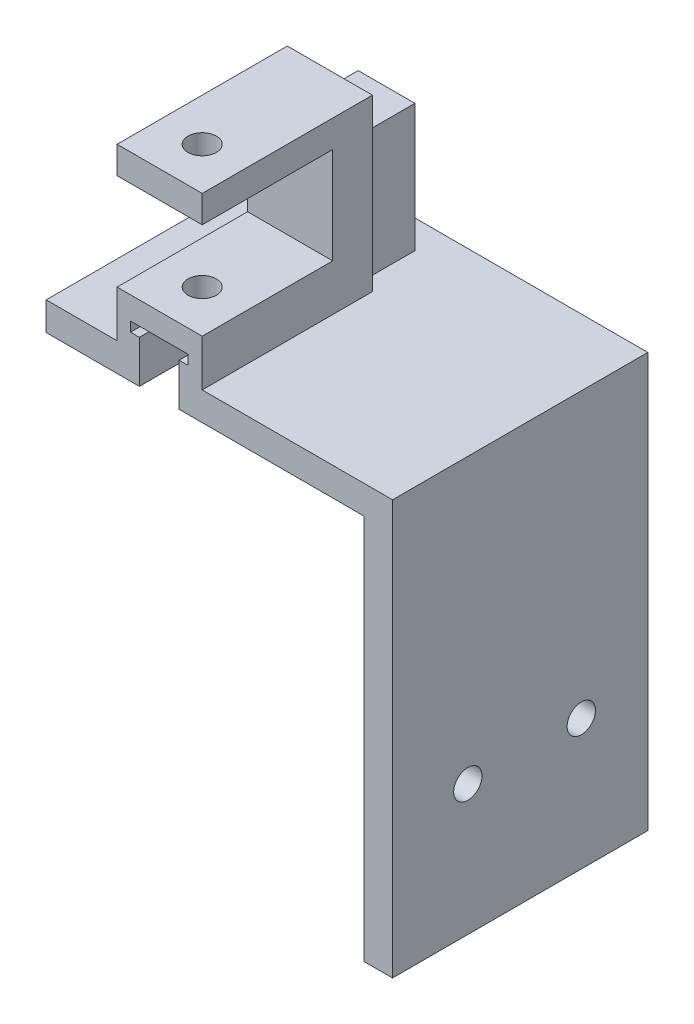
SolidWorks part; units mm, degrees
ref_plane "Front Plane" through (0, 0, 0) normal (0, 0, 1) x (1, 0, 0)
ref_plane "Top Plane" through (0, 0, 0) normal (0, 1, 0) x (1, 0, 0)
ref_plane "Right Plane" through (0, 0, 0) normal (1, 0, 0) x (0, 0, -1)
sketch "Sketch1" plane through (0, 0, 0) normal (0, 1, 0) x (1, 0, 0)
  line L1 (0, 0) -> (61.05, 0)
  line L2 (0, 0) -> (0, 45)
  line L3 (0, 45) -> (61.05, 45)
  line L4 (61.05, 0) -> (61.05, 45)
  dimension "D1" = 61.05
  dimension "D2" = 45
extrude "Boss-Extrude2" add sketch "Sketch1" along normal blind 5
sketch "Sketch2" plane through (0, 5, 0) normal (0, 1, 0) x (1, 0, 0)
  line L0 (0, 45) -> (0, 0) construction
  line L1 (15, 40) -> (25, 40)
  line L2 (15, 40) -> (15, 30)
  line L3 (15, 30) -> (25, 30)
  line L4 (25, 40) -> (25, 30)
  line L5 (61.05, 45) -> (0, 45) construction
  dimension "D1" = 10
  dimension "D2" = 10
  dimension "D3" = 5
  dimension "D4" = 15
extrude "Boss-Extrude3" add sketch "Sketch2" along normal blind 22.5
sketch "Sketch3" plane through (0, 0, -40) normal (0, 0, -1) x (-1, 0, 0)
  line L0 (-25, 27.5) -> (-25, 5) construction
  line L2 (-25, 5) -> (-15, 5) construction
  circle A0 centre (-20, 20.9) radius 4
  dimension "D1" = 8
  dimension "D2" = 5
  dimension "D3" = 15.9
extrude "Cut-Extrude1" cut sketch "Sketch3" against normal blind 8
sketch "Sketch6" plane through (0, 5, 0) normal (0, 1, 0) x (1, 0, 0)
  line L0 (15, 30) -> (25, 30) construction
  line L1 (12.5, 30) -> (27.5, 30)
  line L2 (12.5, 30) -> (12.5, 0)
  line L3 (12.5, 0) -> (27.5, 0)
  line L4 (27.5, 30) -> (27.5, 0)
  line L5 (0, 0) -> (61.05, 0) construction
  line L7 (0, 45) -> (0, 0) construction
  dimension "D1" = 0
  dimension "D2" = 0
  dimension "D3" = 12.5
  dimension "D4" = 15
extrude "Boss-Extrude4" add sketch "Sketch6" along normal blind 30
sketch "Sketch7" plane through (0, 0, 0) normal (0, 0, 1) x (1, 0, 0)
  line L0 (27.5, 5) -> (61.05, 5) construction
  line L1 (27.5, 30.2) -> (12.5, 30.2)
  line L2 (27.5, 30.2) -> (27.5, 13.2)
  line L3 (27.5, 13.2) -> (12.5, 13.2)
  line L4 (12.5, 30.2) -> (12.5, 13.2)
  line L6 (12.5, 35) -> (12.5, 5) construction
  line L7 (27.5, 35) -> (27.5, 5) construction
  dimension "D1" = 8.2
  dimension "D2" = 17
  dimension "D3" = 0
  dimension "D4" = 0
extrude "Cut-Extrude3" cut sketch "Sketch7" against normal blind 23
sketch "Sketch8" plane through (0, 35, 0) normal (0, 1, 0) x (1, 0, 0)
  line L0 (12.5, 0) -> (27.5, 0) construction
  line L1 (0, 45) -> (0, 0) construction
  circle A0 centre (20, 7.5) radius 2.5
  dimension "D1" = 5
  dimension "D2" = 7.5
  dimension "D3" = 20
extrude "Cut-Extrude4" cut sketch "Sketch8" against normal through all
sketch "Sketch9" plane through (0, 0, 0) normal (0, -1, 0) x (1, 0, 0)
  line L0 (61.05, -45) -> (0, -45) construction
  line L1 (61.05, 0) -> (56.05, 0)
  line L2 (61.05, 0) -> (61.05, -45)
  line L3 (61.05, -45) -> (56.05, -45)
  line L4 (56.05, 0) -> (56.05, -45)
  dimension "D1" = 5
extrude "Boss-Extrude5" add sketch "Sketch9" along normal blind 68
sketch "Sketch10" plane through (61.05, 0, 0) normal (1, 0, 0) x (0, 0, -1)
  line L0 (0, 5) -> (30, 5) construction
  circle A0 centre (13.2742, -45) radius 2.5
  circle A1 centre (33.2742, -45) radius 2.5
  dimension "D1" = 5
  dimension "D2" = 5
  dimension "D3" = 20
  dimension "D4" = 0
  dimension "D5" = 50
extrude "Cut-Extrude5" cut sketch "Sketch10" against normal up to surface (5 mm away) up to face at (56.05, -34, -22.5)
sketch "Sketch11" plane through (0, 0, 0) normal (0, 0, 1) x (1, 0, 0)
  line L0 (24.9792, 9.2) -> (14.8792, 9.2)
  line L1 (14.8792, 9.2) -> (14.8792, 7.5)
  line L2 (14.8792, 7.5) -> (16.4292, 7.5)
  line L3 (16.4292, 7.5) -> (16.4292, -2.9441)
  line L4 (16.4292, -2.9441) -> (23.4292, -2.9441)
  line L5 (23.4292, -2.9441) -> (23.4292, 7.5)
  line L6 (23.4292, 7.5) -> (24.9792, 7.5)
  line L7 (24.9792, 7.5) -> (24.9792, 9.2)
  line L8 (12.5, 13.2) -> (27.5, 13.2) construction
  point P7 (0, 0)
  dimension "D1" = 10.1
  dimension "D2" = 1.7
  dimension "D3" = 7
  dimension "D4" = 1.55
  dimension "D5" = 1.7
  dimension "D6" = 4
extrude "Cut-Extrude6" cut sketch "Sketch11" against normal blind 16
